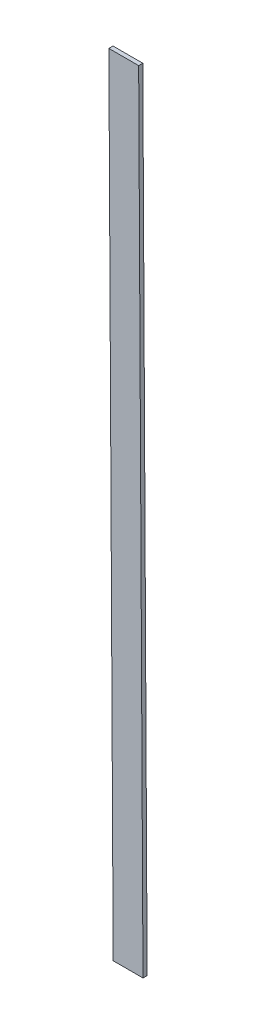
SolidWorks part; units mm, degrees
material "Balsa"
ref_plane "Front Plane" through (0, 0, 0) normal (0, 0, 1) x (1, 0, 0)
ref_plane "Top Plane" through (0, 0, 0) normal (0, 1, 0) x (1, 0, 0)
ref_plane "Right Plane" through (0, 0, 0) normal (1, 0, 0) x (0, 0, -1)
sketch "Sketch1" plane through (0, 0, 0) normal (0, 0, 1) x (1, 0, 0)
  line L0 (-14.6292, -88.4603) -> (-26.0631, -88.4603)
  line L1 (-26.0631, -88.4603) -> (-27.7283, 213.8068)
  line L2 (-27.7283, 213.8068) -> (-16.2944, 213.8068)
  line L3 (-16.2944, 213.8068) -> (-14.6292, -88.4603)
extrude "Boss-Extrude1" add sketch "Sketch1" along normal blind 1.5875 contours L3 L0 L1 L2
